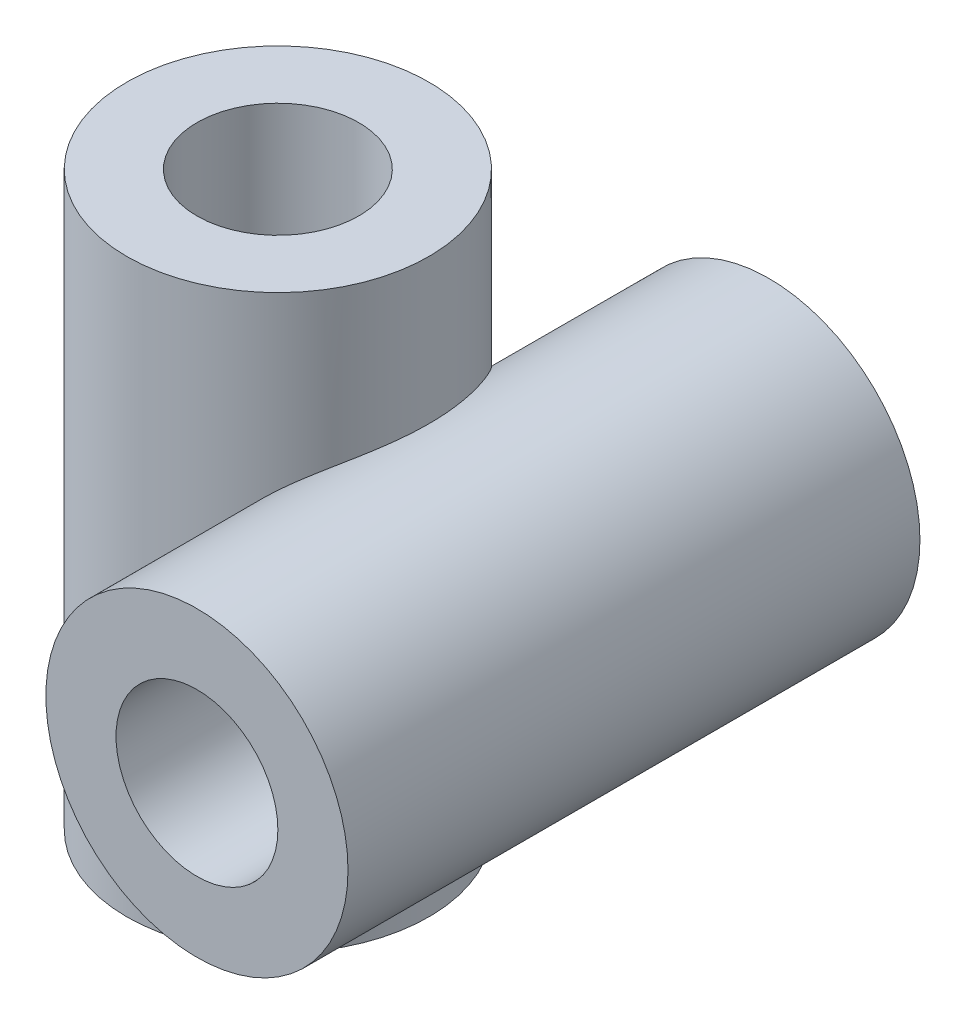
SolidWorks part; units mm, degrees
ref_plane "Front Plane" through (0, 0, 0) normal (0, 0, 1) x (1, 0, 0)
ref_plane "Top Plane" through (0, 0, 0) normal (0, 1, 0) x (1, 0, 0)
ref_plane "Right Plane" through (0, 0, 0) normal (1, 0, 0) x (0, 0, -1)
sketch "Sketch1" plane through (0, 0, 0) normal (0, 0, 1) x (1, 0, 0)
  circle A0 centre (0, 0) radius 15
  circle A1 centre (0, 0) radius 28
extrude "Boss-Extrude1" add sketch "Sketch1" along normal blind 106
sketch "Sketch2" plane through (0, 0, 0) normal (0, 1, 0) x (1, 0, 0)
  line L0 (-28, -53) -> (-38, -53)
  line L1 (-28, 0) -> (-28, -106) construction
  line L2 (-28, -106) -> (-28, 0)
  line L3 (-28, -106) -> (28, -106) construction
  line L4 (28, 0) -> (-28, 0) construction
  circle A0 centre (-38, -53) radius 15
  circle A1 centre (-38, -53) radius 28
extrude "Boss-Extrude3" add sketch "Sketch2" along normal mid plane 106 contours L2 A1 A0 | L2 A1 A0
sketch "Sketch3" plane through (0, 0, 0) normal (0, 0, 1) x (1, 0, 0)
  line L0 (-10, 11.1803) -> (-10, -11.1803)
  circle A0 centre (0, 0) radius 15 construction
  arc A1 (-10, 11.1803) -> (-10, -11.1803) centre (0, 0) ccw
extrude "Cut-Extrude1" cut sketch "Sketch3" against normal mid plane 256 contours A1 L0
sketch "Sketch4" plane through (0, 0, 0) normal (0, 1, 0) x (1, 0, 0)
  line L0 (-28, -64.1803) -> (-28, -41.8197)
  arc A0 (-28, -64.1803) -> (-28, -41.8197) centre (-38, -53) ccw
extrude "Cut-Extrude2" cut sketch "Sketch4" against normal mid plane 246
